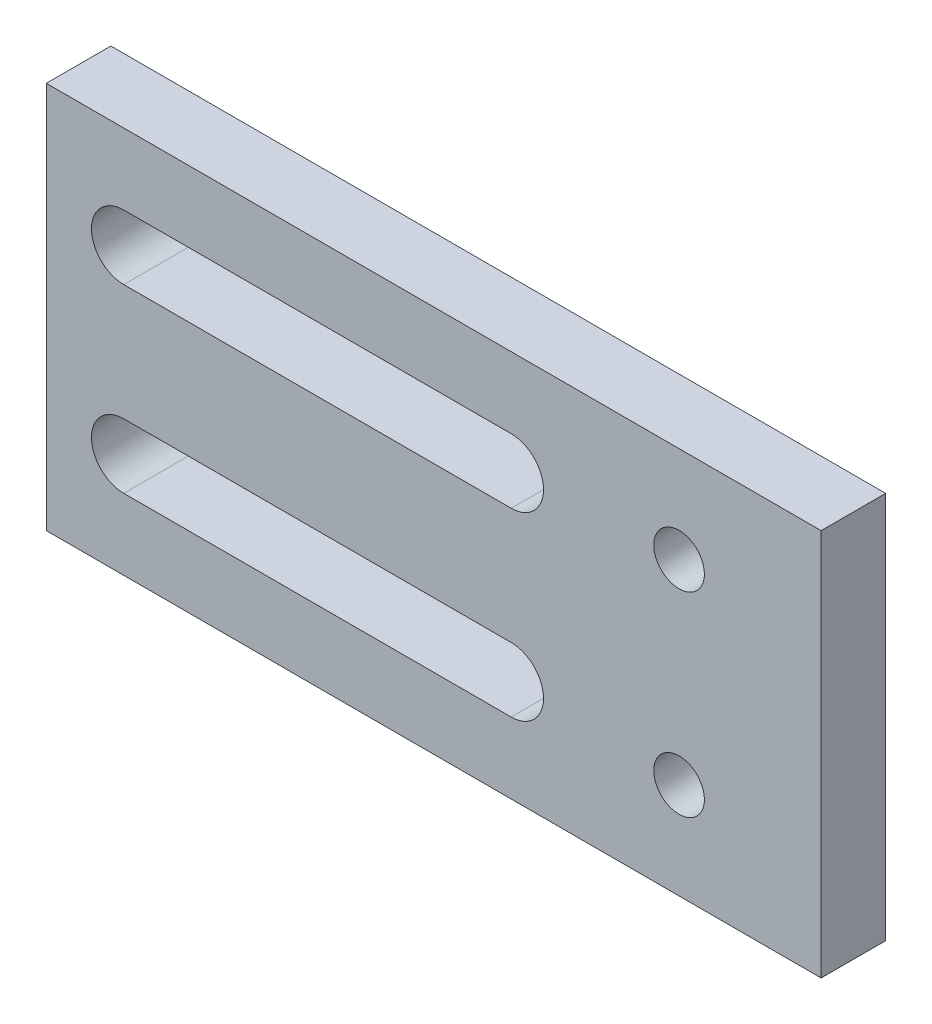
SolidWorks part; units mm, degrees
ref_plane "Front Plane" through (0, 0, 0) normal (0, 0, 1) x (1, 0, 0)
ref_plane "Top Plane" through (0, 0, 0) normal (0, 1, 0) x (1, 0, 0)
ref_plane "Right Plane" through (0, 0, 0) normal (1, 0, 0) x (0, 0, -1)
sketch "Sketch1" plane through (0, 0, 0) normal (0, 0, 1) x (1, 0, 0)
  line L0 (-19.05, 0) -> (19.05, 0) construction
  line L1 (-19.05, 9.525) -> (19.05, 9.525)
  line L2 (-19.05, 9.525) -> (-19.05, -9.525)
  line L3 (-19.05, -9.525) -> (19.05, -9.525)
  line L4 (19.05, 9.525) -> (19.05, -9.525)
  line L5 (-19.05, 9.525) -> (19.05, -9.525) construction
  line L6 (-19.05, -9.525) -> (19.05, 9.525) construction
  line L7 (-19.05, -4.445) -> (19.05, -4.445)
  line L8 (-19.05, 4.445) -> (19.05, 4.445)
  line L9 (-15.24, 2.8575) -> (3.81, 2.8575)
  line L10 (-15.24, 6.0325) -> (3.81, 6.0325)
  line L11 (-15.24, -2.8575) -> (3.81, -2.8575)
  line L12 (-15.24, -6.0325) -> (3.81, -6.0325)
  line L13 (12.065, 4.8006) -> (12.065, -4.8006)
  circle A0 centre (-15.24, 4.445) radius 1.5875
  circle A1 centre (3.81, 4.445) radius 1.5875
  circle A2 centre (3.81, -4.445) radius 1.5875
  circle A3 centre (-15.24, -4.445) radius 1.5875
  circle A4 centre (12.065, 4.8006) radius 1.2446
  circle A5 centre (12.065, -4.8006) radius 1.2446
  point P0 (0, 0)
  point P30 (12.065, 0)
  dimension "D4" = 3.175
  dimension "D6" = 3.175
  dimension "D9" = 2.4892
  dimension "D11" = 2.4892
  dimension "D1" = 19.05
  dimension "D2" = 38.1
  dimension "D3" = 4.445
  dimension "D5" = 3.81
  dimension "D7" = 19.05
  dimension "D8" = 9.6012
  dimension "D10" = 6.985
extrude "Boss-Extrude1" add sketch "Sketch1" along normal blind 3.175
sketch "Sketch2" plane through (0, 0, 3.175) normal (0, 0, 1) x (1, 0, 0)
  line L0 (5.715, 4.8006) -> (5.715, -4.8006)
  line L1 (12.065, 4.8006) -> (12.065, -4.8006) construction
  circle A0 centre (12.065, -4.8006) radius 1.2446 construction
  circle A1 centre (12.065, 4.8006) radius 1.2446 construction
  circle A2 centre (12.065, -4.8006) radius 1.2446
  circle A3 centre (12.065, 4.8006) radius 1.2446
  dimension "D1" = 6.35
